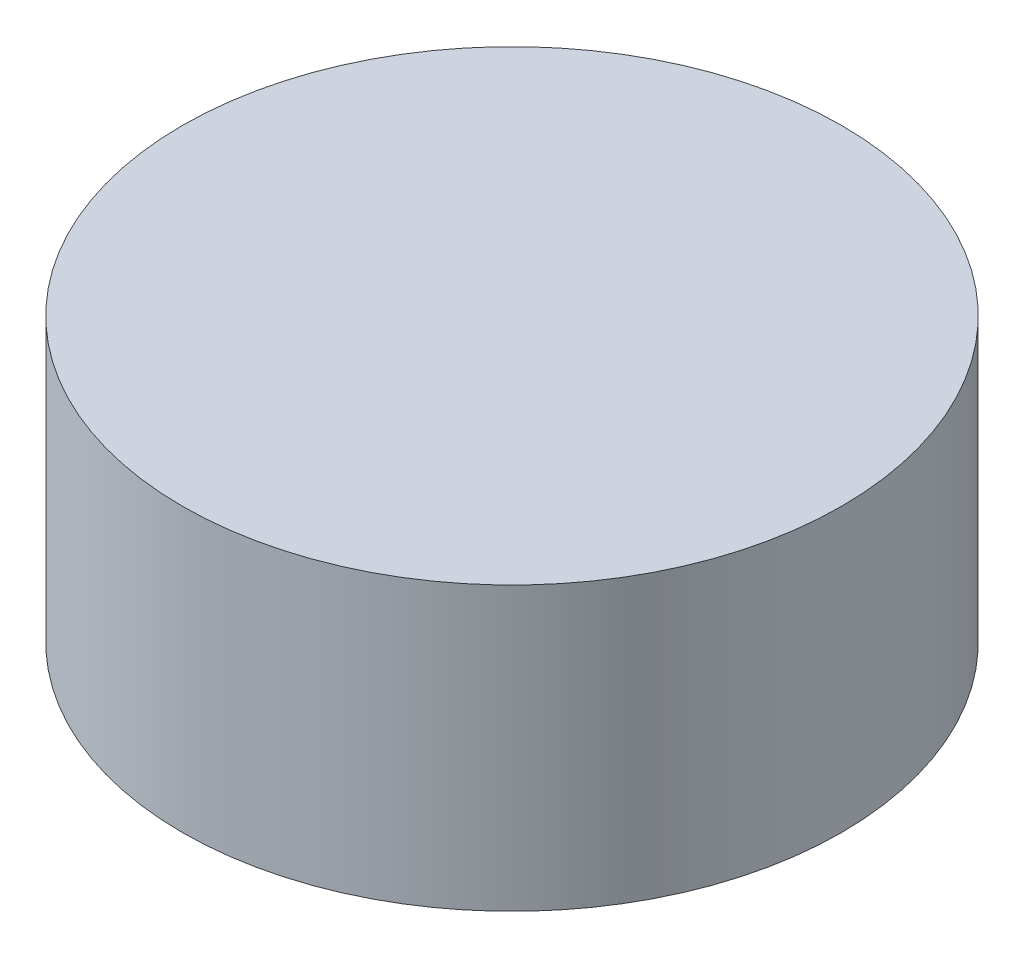
SolidWorks part; units mm, degrees
ref_plane "前视基准面" through (0, 0, 0) normal (0, 0, 1) x (1, 0, 0)
ref_plane "上视基准面" through (0, 0, 0) normal (0, 1, 0) x (1, 0, 0)
ref_plane "右视基准面" through (0, 0, 0) normal (1, 0, 0) x (0, 0, -1)
other "Configuration Table"
sketch "草图1" plane through (0, 0, 0) normal (0, 0, 1) x (1, 0, 0)
  line L0 (0, 0) -> (3.5, 0)
  line L1 (3.5, 0) -> (3.5, 3)
  line L2 (3.5, 3) -> (0, 3)
  line L3 (0, 3) -> (0, 0)
  line L4 (0, 0) -> (0, 3) construction
  dimension "radius" = 3.5
  dimension "height" = 3
revolve "Revolve" add sketch "草图1" angle 360 about L4
